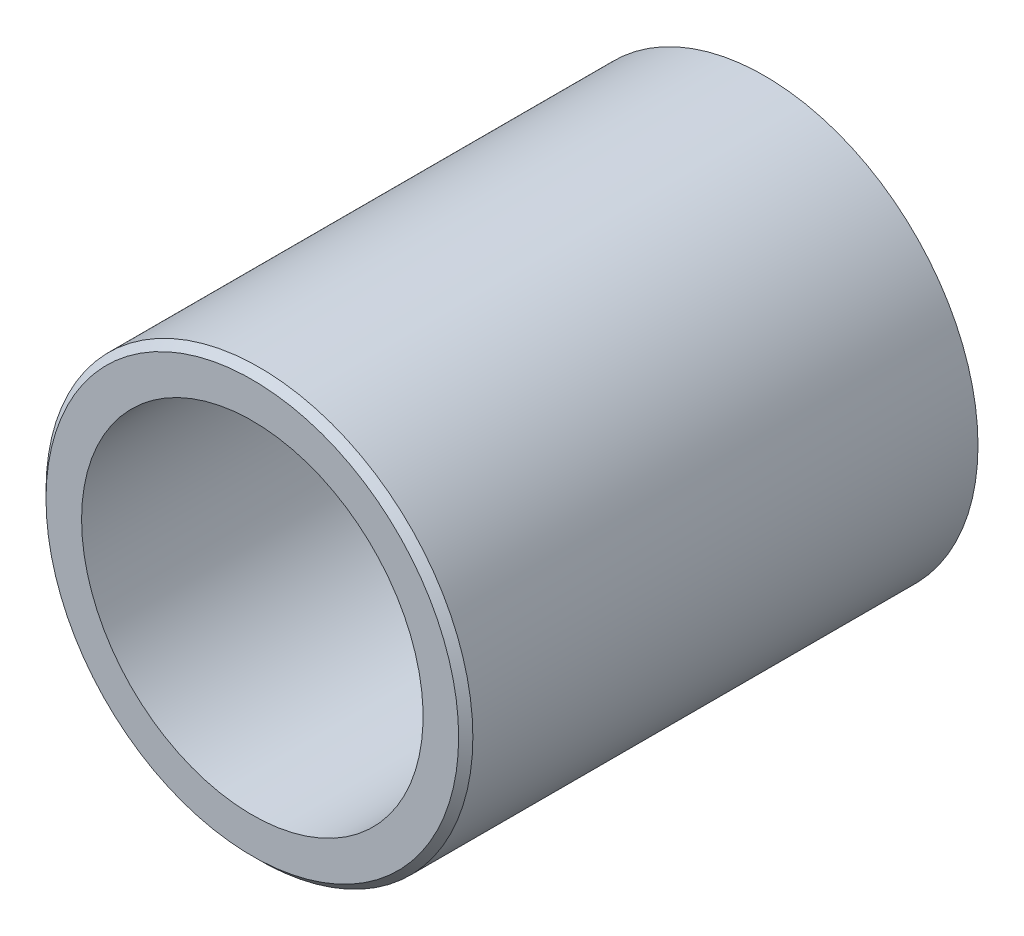
SolidWorks part; units mm, degrees
ref_plane "Front Plane" through (0, 0, 0) normal (0, 0, 1) x (1, 0, 0)
ref_plane "Top Plane" through (0, 0, 0) normal (0, 1, 0) x (1, 0, 0)
ref_plane "Right Plane" through (0, 0, 0) normal (1, 0, 0) x (0, 0, -1)
sketch "Sketch1" plane through (0, 0, 0) normal (0, 0, 1) x (1, 0, 0)
  line L0 (0, 6.35) -> (0, 7.9375) construction
  circle A0 centre (0, 0) radius 7.9375
  circle A1 centre (0, 0) radius 6.35
  dimension "D1" = 1.5875
  dimension "OD" = 15.875
  dimension "ID" = 12.7
extrude "Extrude1" add sketch "Sketch1" along normal mid plane 19.05
chamfer "Chamfer1" distance 0.2646 angle 45 1 edges at (7.9375, 0, 9.525)
sketch "Sketch6" plane through (0, 0, 9.525) normal (0, 0, -1) x (-1, 0, 0)
  line L0 (0, 0) -> (-6.35, 0) construction
  line L1 (0, 0) -> (4.4901, 4.4901) construction
  circle A0 centre (0, 0) radius 6.35 construction
  circle A3 centre (0, 0) radius 6.35
  dimension "D1" = 135
equation "\"D1@Chamfer1\" = \"D1@Sketch1\"/6"
